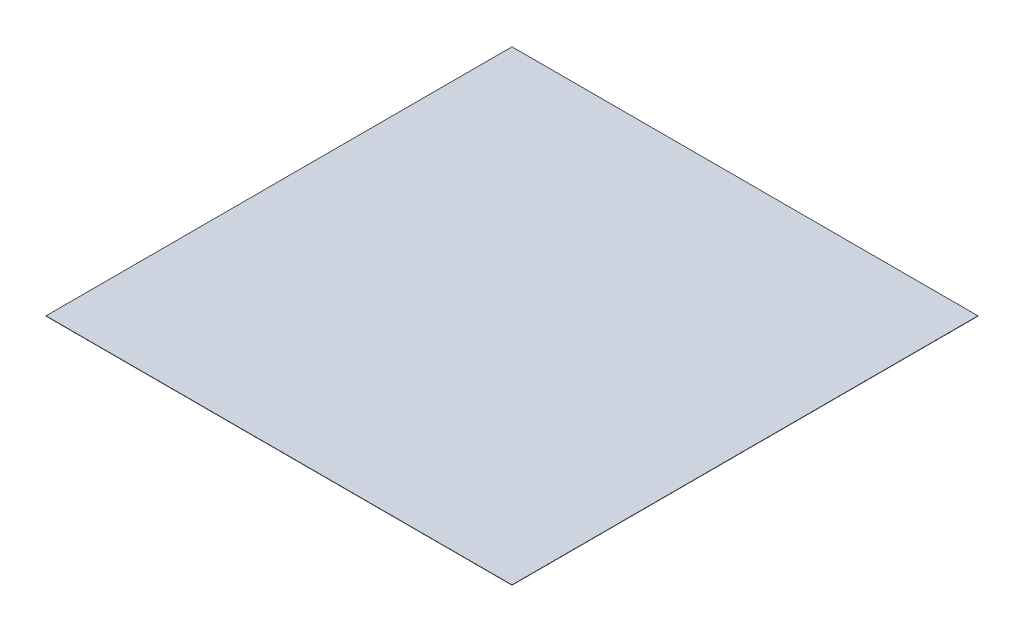
SolidWorks part; units mm, degrees
material "Corrugated Paper"
ref_plane "Front Plane" through (0, 0, 0) normal (0, 0, 1) x (1, 0, 0)
ref_plane "Top Plane" through (0, 0, 0) normal (0, 1, 0) x (1, 0, 0)
ref_plane "Right Plane" through (0, 0, 0) normal (1, 0, 0) x (0, 0, -1)
sketch "Sketch1" plane through (0, 0, 0) normal (0, 1, 0) x (1, 0, 0)
  line L1 (85, -85) -> (-85, -85)
  line L2 (85, -85) -> (85, 85)
  line L3 (85, 85) -> (-85, 85)
  line L4 (-85, -85) -> (-85, 85)
  line L5 (85, -85) -> (-85, 85) construction
  line L6 (85, 85) -> (-85, -85) construction
  point P0 (0, 0)
  dimension "D1" = 170
  dimension "D2" = 170
extrude "Boss-Extrude1" add sketch "Sketch1" along normal blind 0.1
